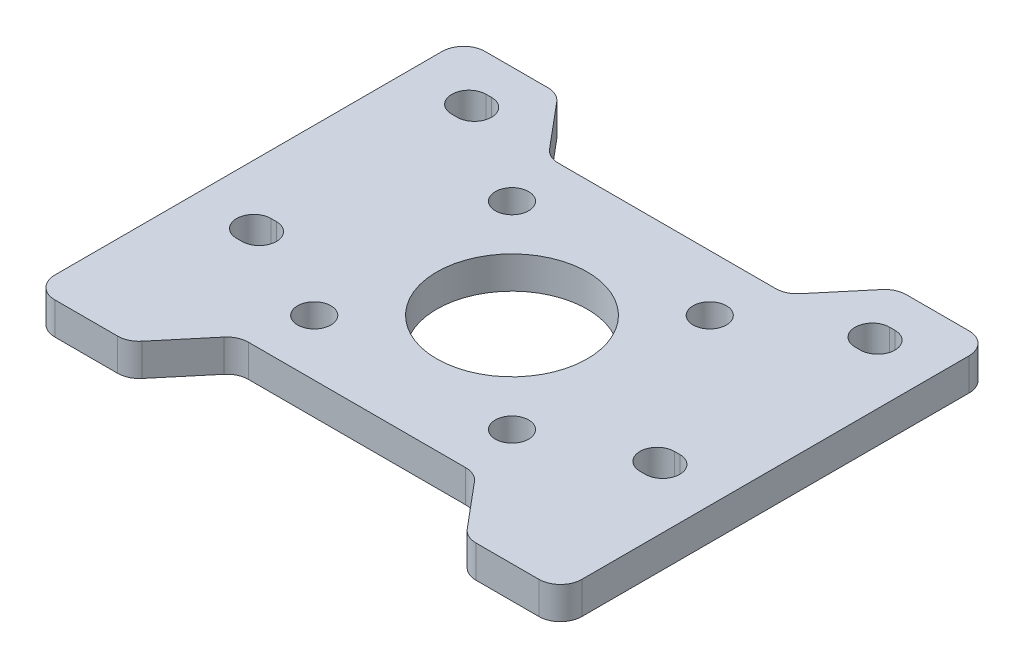
SolidWorks part; units mm, degrees
material "Hexcel AS4C (3000 丝)"
ref_plane "前视基准面" through (0, 0, 0) normal (0, 0, 1) x (1, 0, 0)
ref_plane "上视基准面" through (0, 0, 0) normal (0, 1, 0) x (1, 0, 0)
ref_plane "右视基准面" through (0, 0, 0) normal (1, 0, 0) x (0, 0, -1)
sketch "草图1" plane through (0, 0, 0) normal (0, 1, 0) x (1, 0, 0)
  line L0 (0, 0) -> (0, 26.4141) construction
  line L1 (-19, 20) -> (-19, 0) construction
  line L2 (-19, 0) -> (19, 0) construction
  line L3 (-19, 20) -> (19, 0) construction
  line L4 (-19, 20) -> (-18.5, 20) construction
  line L9 (-24.5, 25) -> (24.5, 25)
  line L10 (-24.5, 25) -> (-24.5, -15)
  line L11 (-24.5, -15) -> (24.5, -15)
  line L12 (24.5, 25) -> (24.5, -15)
  line L13 (-24.5, 25) -> (24.5, -15) construction
  line L14 (-24.5, -15) -> (24.5, 25) construction
  line L15 (-19, 21.6) -> (-18.5, 21.6)
  line L16 (-19, 18.4) -> (-18.5, 18.4)
  line L17 (19, 20) -> (18.5, 20) construction
  line L18 (19, 18.4) -> (18.5, 18.4)
  line L19 (19, 21.6) -> (18.5, 21.6)
  line L20 (-19, 10) -> (-8.5112, 10) construction
  line L21 (19, 0) -> (18.5, 0) construction
  line L22 (19, 1.6) -> (18.5, 1.6)
  line L23 (19, -1.6) -> (18.5, -1.6)
  line L24 (-19, 0) -> (-18.5, 0) construction
  line L25 (-19, -1.6) -> (-18.5, -1.6)
  line L26 (-19, 1.6) -> (-18.5, 1.6)
  circle A0 centre (-19, 20) radius 1.6 construction
  circle A1 centre (-19, 0) radius 1.6 construction
  circle A2 centre (19, 20) radius 1.6 construction
  circle A3 centre (19, 0) radius 1.6 construction
  arc A4 (-19, 21.6) -> (-19, 18.4) centre (-19, 20) ccw
  arc A5 (-18.5, 18.4) -> (-18.5, 21.6) centre (-18.5, 20) ccw
  arc A6 (19, 18.4) -> (19, 21.6) centre (19, 20) ccw
  arc A7 (18.5, 21.6) -> (18.5, 18.4) centre (18.5, 20) ccw
  arc A8 (19, 1.6) -> (19, -1.6) centre (19, 0) cw
  arc A9 (18.5, -1.6) -> (18.5, 1.6) centre (18.5, 0) cw
  arc A10 (-19, -1.6) -> (-19, 1.6) centre (-19, 0) cw
  arc A11 (-18.5, 1.6) -> (-18.5, -1.6) centre (-18.5, 0) cw
  point P11 (0, 10)
  point P12 (0, 5)
  point P17 (-18.75, 20)
  point P23 (18.75, 20)
  point P32 (18.75, 0)
  point P38 (-18.75, 0)
  dimension "D1" = 38
  dimension "D2" = 3.2
  dimension "D4" = 5
  dimension "D7" = 1.6
  dimension "D9" = 1.6
  dimension "D3" = 20
  dimension "D5" = 49
  dimension "D6" = 40
  dimension "D8" = 0.5
  dimension "D10" = 0.5
extrude "凸台-拉伸1" add sketch "草图1" along normal blind 3
sketch "草图2" plane through (0, 3, 0) normal (0, 1, 0) x (1, 0, 0)
  line L0 (-24.5, 25) -> (24.5, -15) construction
  line L1 (24.5, 25) -> (-24.5, -15) construction
  line L2 (0, 5) -> (24.5, 5) construction
  line L3 (24.5, -15) -> (24.5, 25) construction
  line L4 (0, 5) -> (0, 25) construction
  line L5 (24.5, 25) -> (-24.5, 25) construction
  line L6 (0, 5) -> (9.1924, 14.1924) construction
  circle A0 centre (0, 5) radius 13 construction
  circle A1 centre (9.1924, 14.1924) radius 1.55
  circle A2 centre (9.1924, -4.1924) radius 1.55
  circle A3 centre (-9.1924, 14.1924) radius 1.55
  circle A4 centre (-9.1924, -4.1924) radius 1.55
  circle A5 centre (0, 5) radius 7
  dimension "D1" = 26
  dimension "D2" = 3.1
  dimension "D4" = 14
  dimension "D3" = 45
extrude "切除-拉伸1" cut sketch "草图2" against normal through all
sketch "草图3" plane through (0, 3, 0) normal (0, 1, 0) x (1, 0, 0)
  line L0 (0, 5) -> (0, 25) construction
  line L1 (24.5, 25) -> (-24.5, 25) construction
  line L2 (-15.7213, 25) -> (-11.0367, 19.4112)
  line L3 (-11.0367, 19.4112) -> (11.0367, 19.4112)
  line L4 (15.7213, 25) -> (11.0367, 19.4112)
  line L5 (15.7213, 25) -> (-15.7213, 25)
  line L6 (0, -15) -> (0, 5) construction
  line L7 (-24.5, -15) -> (24.5, -15) construction
  line L8 (0, 5) -> (24.5, 5) construction
  line L9 (24.5, -15) -> (24.5, 25) construction
  line L10 (15.7213, -15) -> (11.0367, -9.4112)
  line L11 (-11.0367, -9.4112) -> (11.0367, -9.4112)
  line L12 (-15.7213, -15) -> (-11.0367, -9.4112)
  line L13 (15.7213, -15) -> (-15.7213, -15)
  point P10 (0, 19.4112)
extrude "切除-拉伸2" cut sketch "草图3" against normal through all
fillet "圆角1" radius 2 12 edges at (-11.0367, 1.5, -19.4112) (-15.7213, 1.5, -25) (-24.5, 1.5, -25) (-24.5, 1.5, 15) (-15.7213, 1.5, 15) (11.0367, 1.5, 9.4112) (15.7213, 1.5, 15) (24.5, 1.5, 15) (24.5, 1.5, -25) (15.7213, 1.5, -25) (11.0367, 1.5, -19.4112) (-11.0367, 1.5, 9.4112)
